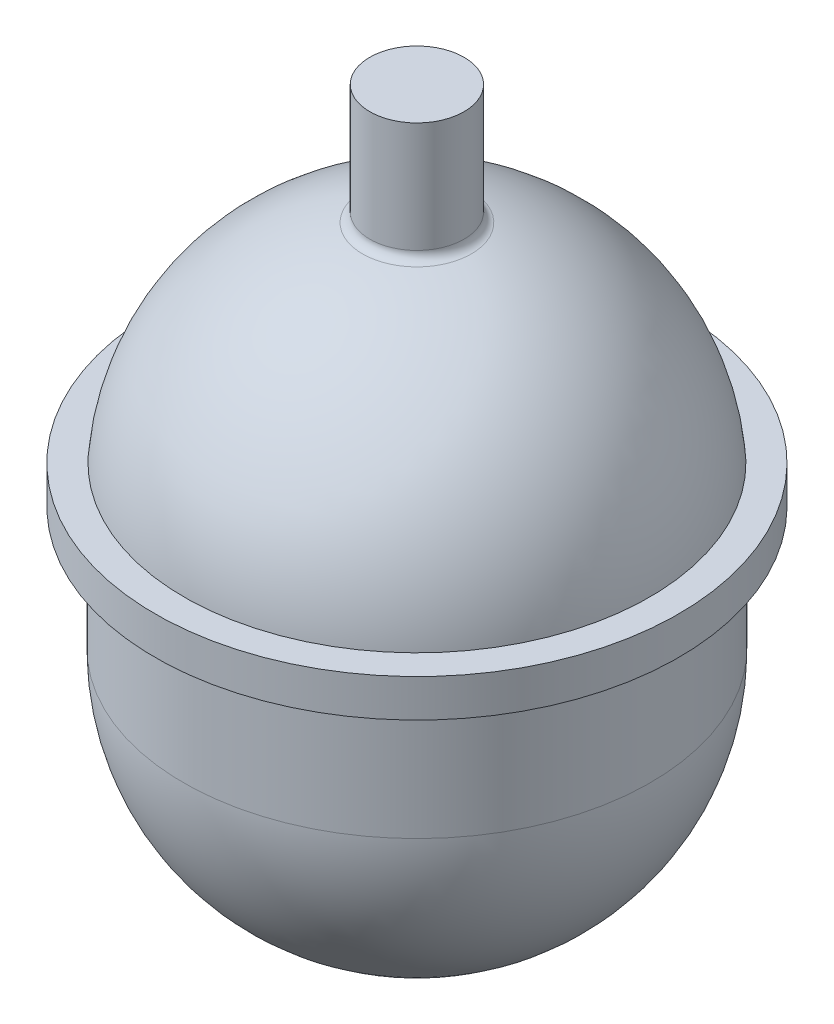
SolidWorks part; units mm, degrees
ref_plane "Front Plane" through (0, 0, 0) normal (0, 0, 1) x (1, 0, 0)
ref_plane "Top Plane" through (0, 0, 0) normal (0, 1, 0) x (1, 0, 0)
ref_plane "Right Plane" through (0, 0, 0) normal (1, 0, 0) x (0, 0, -1)
sketch "Sketch1" plane through (0, 0, 0) normal (0, 0, 1) x (1, 0, 0)
  line L1 (55, 0) -> (-55, 0) construction
  line L2 (0, -55) -> (0, 55) construction
  line L3 (-49.5, -4) -> (-49.5, -30)
  line L5 (49.5, 0) -> (49.5, -30) construction
  line L6 (45.5, 0) -> (45.5, -30) construction
  line L7 (0, 45.5) -> (0, 49.5)
  line L8 (0, -75.5) -> (0, -79.5)
  line L10 (-55.5, 0) -> (-55.5, 4)
  line L11 (-55.5, 4) -> (-49.3381, 4)
  line L12 (-55.5, 0) -> (-55.5, -4)
  line L13 (-55.5, -4) -> (-49.5, -4)
  line L14 (-45.5, 0) -> (-45.5, -30)
  arc A0 (-49.5, 0) -> (49.5, 0) centre (0, 0) cw construction
  arc A1 (-45.5, 0) -> (45.5, 0) centre (0, 0) cw construction
  arc A2 (-45.5, -30) -> (45.5, -30) centre (0, -30) ccw construction
  arc A4 (-49.5, -30) -> (49.5, -30) centre (0, -30) ccw construction
  arc A5 (0, -79.5) -> (-49.5, -30) centre (0, -30) cw
  arc A6 (0, -75.5) -> (-45.5, -30) centre (0, -30) cw
  arc A7 (-45.5, 0) -> (0, 45.5) centre (0, 0) cw
  arc A8 (-49.3381, 4) -> (0, 49.5) centre (0, 0) cw
  point P8 (0, 0)
  dimension "D1" = 49.5
  dimension "D4" = 4
  dimension "D5" = 6
  dimension "D6" = 4
  dimension "D2" = 4
ref_axis "Axis1" through (0, -85.95, 0) along (0, 1, 0)
revolve "Revolve2" add sketch "Sketch1" angle 360 about axis through (0, -85.95, 0) along (0, 1, 0)
ref_plane "Plane1" through (0, 49.5, 0) normal (0, 1, 0) x (1, 0, 0)
ref_plane "Plane2" through (0, -79.5, 0) normal (0, -1, 0) x (-1, 0, 0)
ref_plane "Plane3" through (0, 47.5, 0) normal (0, 1, 0) x (1, 0, 0)
ref_plane "Plane4" through (0, -77.5, 0) normal (0, -1, 0) x (-1, 0, 0)
sketch "Sketch2" plane through (0, 47.5, 0) normal (0, 1, 0) x (1, 0, 0)
  circle A0 centre (0, 0) radius 10
  dimension "D1" = 20
extrude "Boss-Extrude1" add sketch "Sketch2" along normal blind 26
sketch "Sketch3" plane through (0, -77.5, 0) normal (0, -1, 0) x (-1, 0, 0)
  circle A0 centre (0, 0) radius 5
  circle A1 centre (0, 0) radius 2
  dimension "D1" = 4
extrude "Boss-Extrude2" add sketch "Sketch3" along normal blind 5
fillet "Fillet1" radius 2 1 edges at (0, 48.4794, -10)
fillet "Fillet3" radius 1 1 edges at (0, -79.2468, 5)
